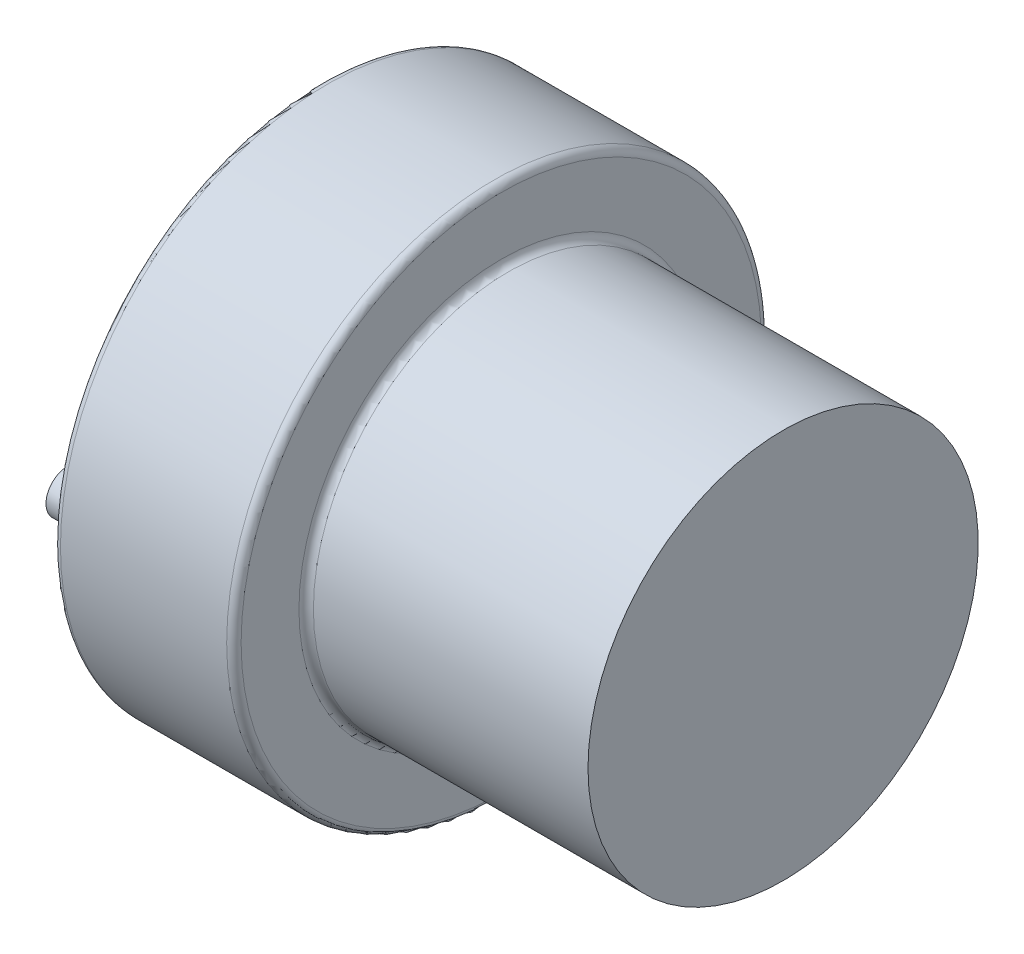
SolidWorks part; units mm, degrees
ref_plane "Front Plane" through (0, 0, 0) normal (0, 0, 1) x (1, 0, 0)
ref_plane "Top Plane" through (0, 0, 0) normal (0, 1, 0) x (1, 0, 0)
ref_plane "Right Plane" through (0, 0, 0) normal (1, 0, 0) x (0, 0, -1)
sketch "Sketch1" plane through (0, 0, 0) normal (0, 0, 1) x (1, 0, 0)
  line L0 (-66.5635, 0) -> (111.2065, 0) construction
  line L1 (86.3215, 27) -> (47.3215, 27)
  line L3 (22.3215, 0) -> (22.3215, 37)
  line L4 (22.3215, 37) -> (47.3215, 37)
  line L5 (47.3215, 37) -> (47.3215, 27)
  line L7 (86.3215, 27) -> (86.3215, 0)
  line L8 (86.3215, 0) -> (22.3215, 0)
  dimension "D1" = 25
  dimension "D3" = 37
revolve "Revolve1" add sketch "Sketch1" angle 360 about L0
sketch "Sketch3" plane through (22.3215, 0, 0) normal (-1, 0, 0) x (0, 0, 1)
  line L0 (0, -29.8) -> (0, -37) construction
  circle A1 centre (0, -29.8) radius 6
  circle A2 centre (0, 0) radius 37 construction
extrude "Boss-Extrude1" add sketch "Sketch3" along normal blind 10
fillet "Fillet1" radius 1 2 edges at (22.3215, -29.8, -6) (12.3215, -29.8, 6)
fillet "Fillet2" radius 1 3 edges at (47.3215, 0, 27) (47.3215, 0, 37) (22.3215, 0, 37)
sketch "Sketch4" plane through (12.3215, 0, 0) normal (-1, 0, 0) x (0, 0, 1)
  circle A0 centre (0, -29.8) radius 3
extrude "Boss-Extrude2" add sketch "Sketch4" along normal blind 25
